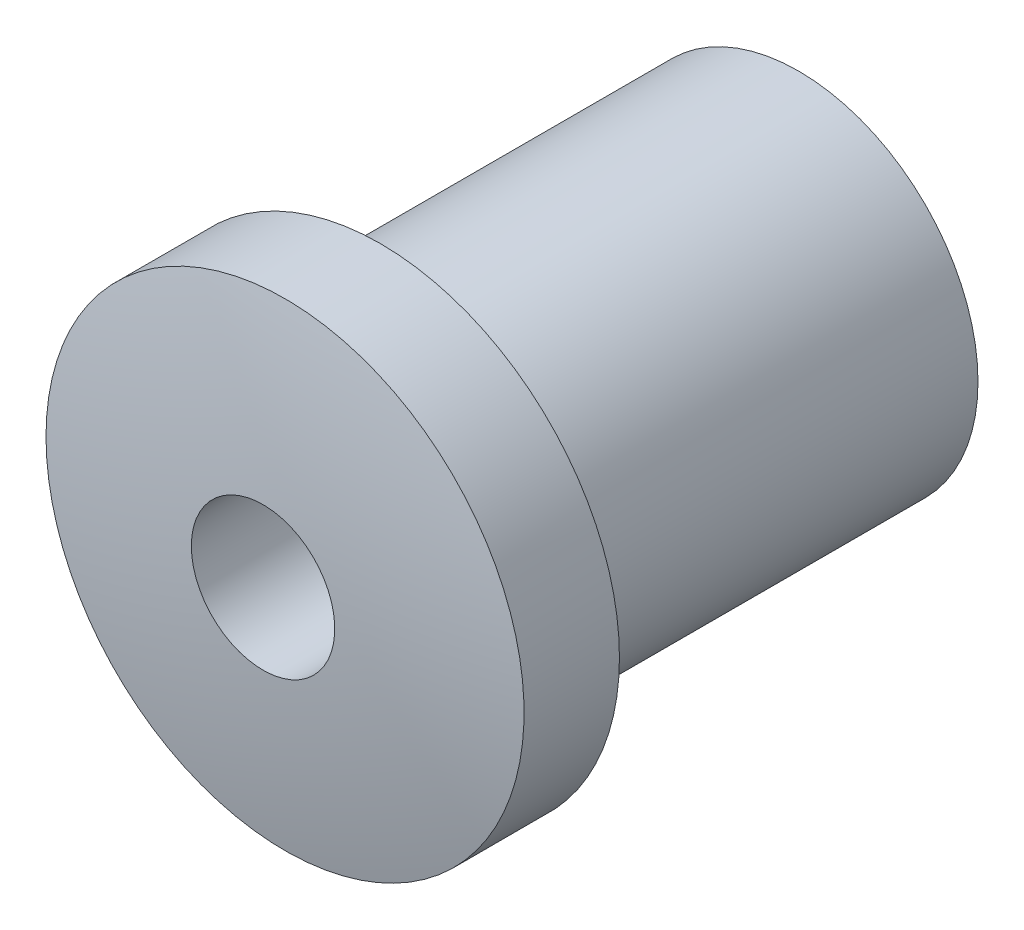
SolidWorks part; units mm, degrees
ref_plane "Piano frontale" through (0, 0, 0) normal (0, 0, 1) x (1, 0, 0)
ref_plane "Piano superiore" through (0, 0, 0) normal (0, 1, 0) x (1, 0, 0)
ref_plane "Piano destro" through (0, 0, 0) normal (1, 0, 0) x (0, 0, -1)
sketch "Sketch1" plane through (0, 0, 0) normal (0, 0, 1) x (1, 0, 0)
  circle A0 centre (0, 0) radius 15
  dimension "D1" = 30
extrude "Boss-Extrude1" add sketch "Sketch1" along normal blind 35
sketch "Sketch5" plane through (0, 0, 0) normal (0, 0, -1) x (-1, 0, 0)
  line L4 (16.5, 0) -> (-16.5, 0) construction
  line L13 (11.0274, 0) -> (5.5137, 9.55)
  line L14 (5.5137, 9.55) -> (-5.5137, 9.55)
  line L15 (-5.5137, 9.55) -> (-11.0274, 0)
  line L16 (-11.0274, 0) -> (-5.5137, -9.55)
  line L17 (-5.5137, -9.55) -> (5.5137, -9.55)
  line L18 (5.5137, -9.55) -> (11.0274, 0)
  line L19 (0, 16.5) -> (0, -16.5) construction
  circle A0 centre (0, 0) radius 9.55 construction
  dimension "D1" = 19.1
extrude "Cut-Extrude1" cut sketch "Sketch5" against normal blind 12
hole_wizard "Ø12.5 (12.5) Diameter Hole1" positions "Sketch9" profile "Sketch8" hole size "Ø12.5" standard "BSI" end condition through all
sketch "Sketch9" plane through (0, 0, 12) normal (0, 0, -1) x (-1, 0, 0)
  point P0 (0, 0)
sketch "Sketch8" plane through (0, 0, 12) normal (1, 0, 0) x (0, 1, 0)
  line L0 (0, 0) -> (0, 23)
  line L1 (0, 23) -> (6.25, 23)
  line L2 (6.25, 23) -> (6.25, 0)
  line L5 (6.25, 0) -> (0, 0)
  line L11 (0, -6.35) -> (0, 107.95) construction
  dimension "Thru Hole Dia." = 12.5
  dimension "Thru Hole Depth" = 23
sketch "Sketch10" plane through (0, 0, 35) normal (0, 0, 1) x (1, 0, 0)
  circle A0 centre (0, 0) radius 20
  circle A2 centre (0, 0) radius 6
  dimension "D1" = 40
  dimension "D2" = 12
extrude "Boss-Extrude2" add sketch "Sketch10" along normal blind 10
sketch "Sketch11" plane through (0, 0, 0) normal (0, 1, 0) x (1, 0, 0)
  line L0 (-20, -45) -> (20, -45) construction
  line L1 (-20, -35) -> (-20, -45) construction
  line L3 (-20, -42.9796) -> (-20, -45)
  line L4 (-20, -45) -> (-6, -45)
  line L5 (-6, -45) -> (6, -45) construction
  line L6 (-6, -45) -> (6, -45) construction
  line L7 (-6, -45) -> (-6, -44.8198)
  line L8 (0, -16.5) -> (0, 16.5) construction
  arc A0 (-6, -44.8198) -> (-20, -42.9796) centre (0, 55) cw
  dimension "D1" = 100
sketch "Sketch13" plane through (0, 0, 0) normal (1, 0, 0) x (0, 0, -1)
  line L0 (0, 0) -> (-29.9402, 0)
  line L1 (-42.9796, 0) -> (-45, 0) construction
revolve "Cut-Revolve6" cut sketch "Sketch11" angle 360 about L0
